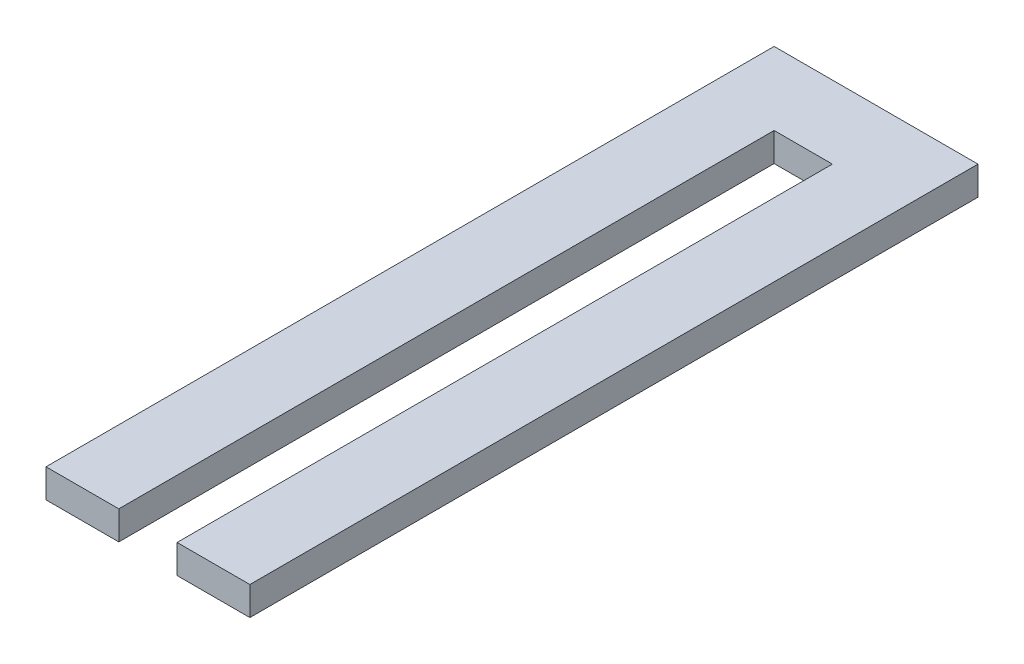
SolidWorks part; units mm, degrees
ref_plane "Front Plane" through (0, 0, 0) normal (0, 0, 1) x (1, 0, 0)
ref_plane "Top Plane" through (0, 0, 0) normal (0, 1, 0) x (1, 0, 0)
ref_plane "Right Plane" through (0, 0, 0) normal (1, 0, 0) x (0, 0, -1)
sketch "Sketch1" plane through (0, 0, 0) normal (0, 1, 0) x (1, 0, 0)
  line L0 (-4.2779, 0) -> (5.8821, 0)
  line L1 (5.8821, 0) -> (5.8821, -114.3)
  line L2 (5.8821, -114.3) -> (18.5821, -114.3)
  line L3 (18.5821, -114.3) -> (18.5821, 12.7)
  line L4 (18.5821, 12.7) -> (-16.9779, 12.7)
  line L5 (-16.9779, 12.7) -> (-16.9779, -114.3)
  line L6 (-16.9779, -114.3) -> (-4.2779, -114.3)
  line L7 (-4.2779, -114.3) -> (-4.2779, 0)
  dimension "D1" = 10.16
  dimension "D2" = 12.7
  dimension "D3" = 12.7
  dimension "D4" = 127
  dimension "D5" = 127
  dimension "D6" = 114.3
extrude "Boss-Extrude1" add sketch "Sketch1" along normal blind 5
